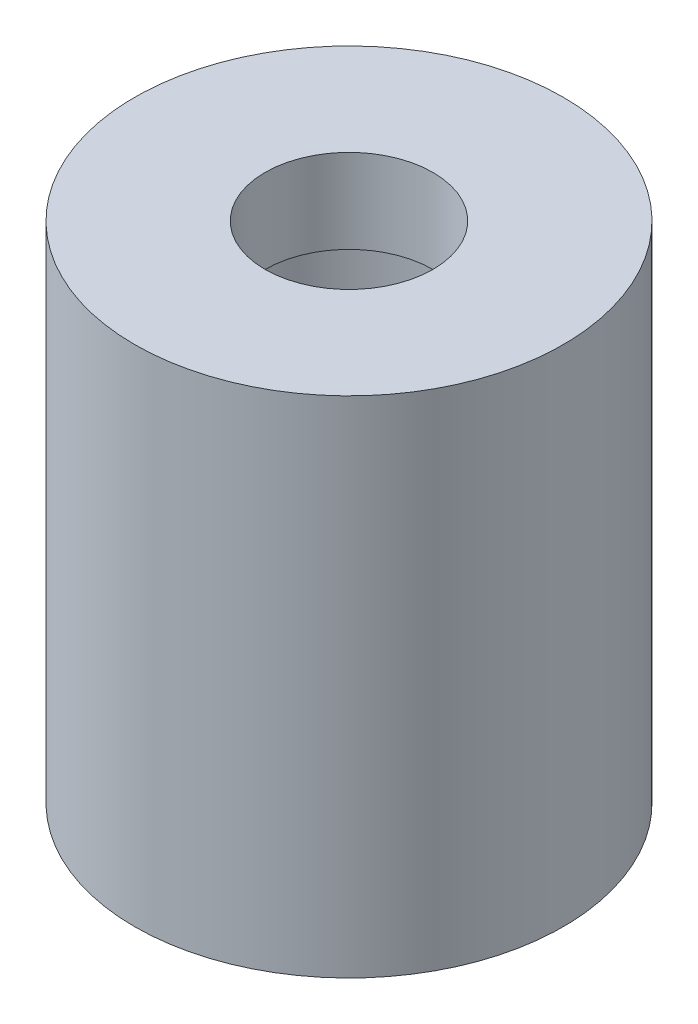
SolidWorks part; units mm, degrees
ref_plane "Front Plane" through (0, 0, 0) normal (0, 0, 1) x (1, 0, 0)
ref_plane "Top Plane" through (0, 0, 0) normal (0, 1, 0) x (1, 0, 0)
ref_plane "Right Plane" through (0, 0, 0) normal (1, 0, 0) x (0, 0, -1)
sketch "Sketch1" plane through (0, 0, 0) normal (0, 1, 0) x (1, 0, 0)
  circle A0 centre (0, 0) radius 6.477
  dimension "D1" = 12.954
extrude "Boss-Extrude3" add sketch "Sketch1" along normal blind 15.24 contours A0
sketch "Sketch4" plane through (0, 0, 0) normal (0, -1, 0) x (1, 0, 0)
  circle A0 centre (0, 0) radius 4.064
  dimension "D1" = 8.128
extrude "Cut-Extrude2" cut sketch "Sketch4" against normal blind 12.7
sketch "Sketch5" plane through (0, 12.7, 0) normal (0, -1, 0) x (1, 0, 0)
  circle A0 centre (0, 0) radius 2.539
extrude "Cut-Extrude3" cut sketch "Sketch5" against normal blind 12.7
sketch "Sketch8" plane through (0, 0, 0) normal (1, 0, 0) x (0, 0, -1)
  line L0 (6.477, 15.24) -> (-6.477, 15.24) construction
  line L1 (-6.4309, 15.24) -> (6.4929, 15.24)
  line L2 (-6.4309, 15.24) -> (-6.4309, 15.8987)
  line L3 (-6.4309, 15.8987) -> (6.4929, 15.8987)
  line L4 (6.4929, 15.24) -> (6.4929, 15.8987)
sketch "Sketch9" plane through (0, 0, 0) normal (0, 0, 1) x (1, 0, 0)
  line L3 (6.472, 19.0597) -> (-6.472, 19.0597)
  line L5 (-6.472, 19.0597) -> (-6.472, 18.415)
  line L6 (6.472, 19.0597) -> (6.472, 18.415)
  line L8 (-6.472, 18.415) -> (6.472, 18.415)
  line L9 (0, 18.415) -> (0, 15.24) construction
  line L10 (0, 15.24) -> (0, 15.8987) construction
  line L11 (0, 15.24) -> (0, 15.8987) construction
  dimension "D1" = 3.175
